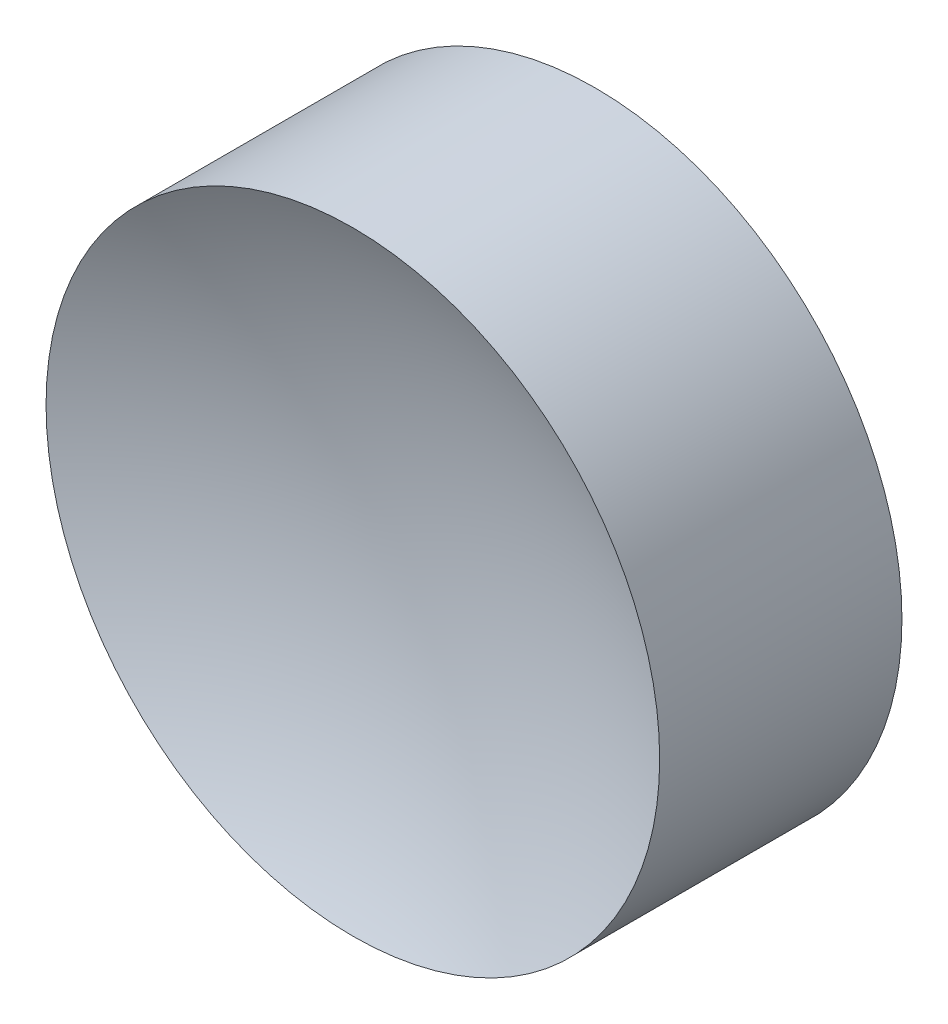
SolidWorks part; units mm, degrees
ref_plane "前视基准面" through (0, 0, 0) normal (0, 0, 1) x (1, 0, 0)
ref_plane "上视基准面" through (0, 0, 0) normal (0, 1, 0) x (1, 0, 0)
ref_plane "右视基准面" through (0, 0, 0) normal (1, 0, 0) x (0, 0, -1)
other "Configuration Table"
sketch "草图1" plane through (0, 0, 0) normal (0, 1, 0) x (1, 0, 0)
  line L0 (0, 0) -> (0, 3.8)
  line L1 (0, 1.9) -> (-12, 1.9) construction
  line L2 (-12, 6.6379) -> (-12, -2.8379)
  arc A0 (0, 0) -> (-12, -2.8379) centre (0, -26.79) ccw
  arc A1 (0, 3.8) -> (-12, 6.6379) centre (0, 30.59) cw
  dimension "D2" = 53.58
  dimension "D1" = 3.8
  dimension "D3" = 12
revolve "旋转1" add sketch "草图1" angle 360 about L0
